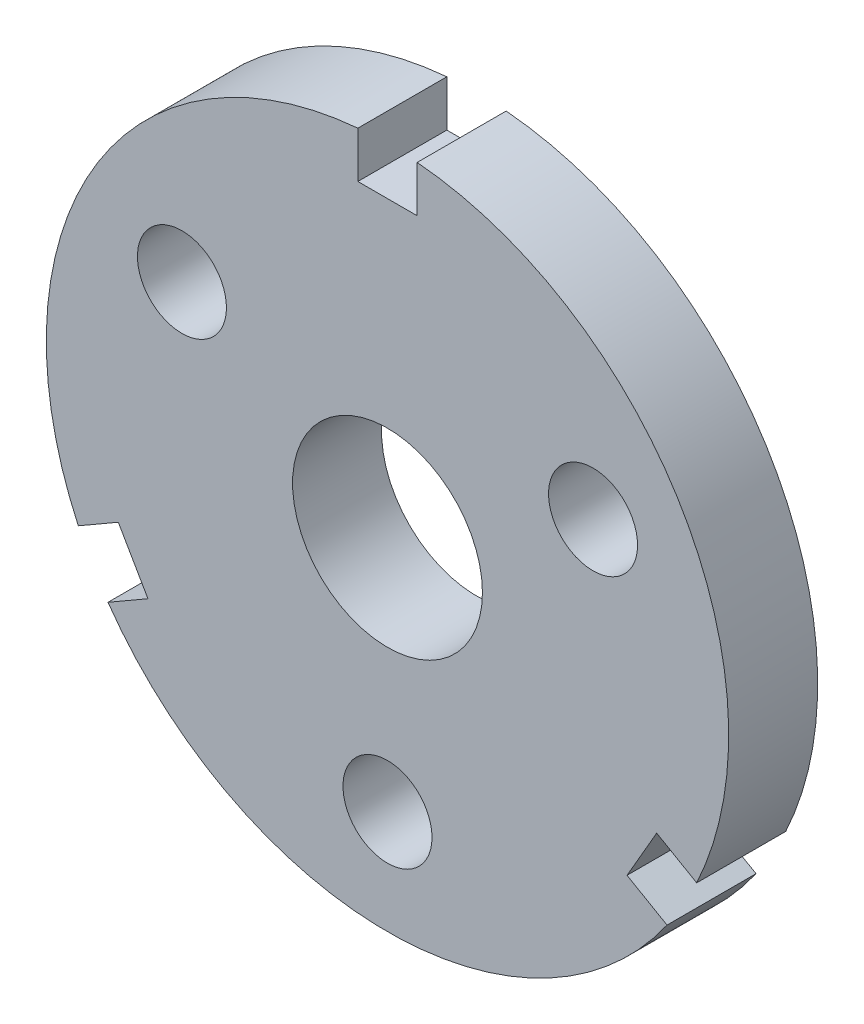
SolidWorks part; units mm, degrees
ref_plane "Płaszczyzna przednia" through (0, 0, 0) normal (0, 0, 1) x (1, 0, 0)
ref_plane "Płaszczyzna górna" through (0, 0, 0) normal (0, 1, 0) x (1, 0, 0)
ref_plane "Płaszczyzna prawa" through (0, 0, 0) normal (1, 0, 0) x (0, 0, -1)
sketch "Szkic1" plane through (0, 0, 0) normal (0, 0, 1) x (1, 0, 0)
  line L0 (0, 0) -> (144.2871, 0) construction
  line L1 (0, 0) -> (91.2553, 52.6863) construction
  line L2 (0, 0) -> (0, 57.5) construction
  line L3 (-5, 57.5) -> (5, 57.5)
  line L4 (-5, 57.5) -> (-5, 49.5)
  line L5 (-5, 49.5) -> (5, 49.5)
  line L6 (5, 49.5) -> (5, 57.5)
  line L7 (45.3683, -20.4199) -> (40.3683, -29.0801)
  line L8 (52.2965, -24.4199) -> (45.3683, -20.4199)
  line L9 (52.2965, -24.4199) -> (47.2965, -33.0801)
  line L10 (40.3683, -29.0801) -> (47.2965, -33.0801)
  line L11 (-40.3683, -29.0801) -> (-45.3683, -20.4199)
  line L12 (-47.2965, -33.0801) -> (-40.3683, -29.0801)
  line L13 (-47.2965, -33.0801) -> (-52.2965, -24.4199)
  line L14 (-45.3683, -20.4199) -> (-52.2965, -24.4199)
  circle A0 centre (0, 0) radius 57.5
  circle A1 centre (0, 0) radius 40
  circle A2 centre (34.641, 20) radius 7.5
  circle A3 centre (0, 0) radius 16
  circle A4 centre (0, -40) radius 7.5
  circle A5 centre (-34.641, 20) radius 7.5
  point P9 (34.641, 20)
  point P12 (0, 0)
  point P17 (0, 0)
  point P31 (0, 0)
  dimension "D1" = 115
  dimension "D2" = 80
  dimension "D4" = 15
  dimension "D5" = 32
  dimension "D3" = 30
  dimension "D7" = 10
  dimension "D8" = 8
  dimension "D6" = 3
  dimension "D9" = 3
extrude "Dodanie-wyciągnięcie1" add sketch "Szkic1" along normal blind 15 contours L4 A0 L14 L11 L12 L10 L7 L8 L6 L5 A5 A1 A2 A4 | A5 A1 A4 A2 A3
